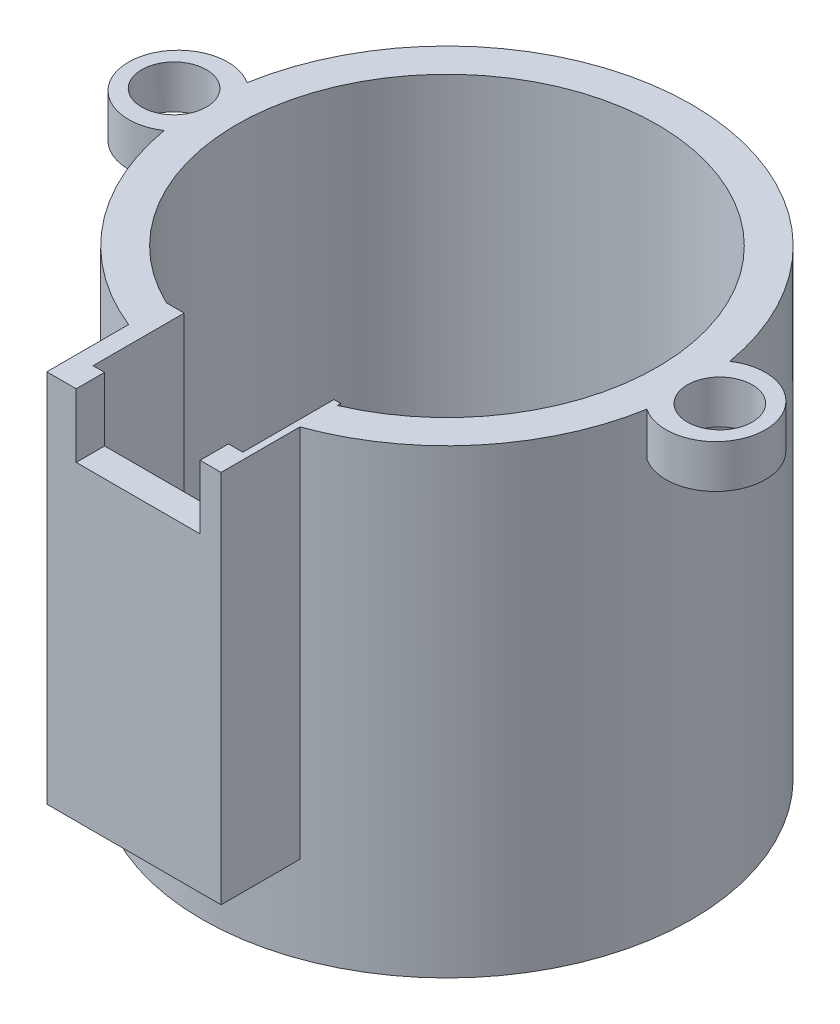
SolidWorks part; units mm, degrees
ref_plane "Front Plane" through (0, 0, 0) normal (0, 0, 1) x (1, 0, 0)
ref_plane "Top Plane" through (0, 0, 0) normal (0, 1, 0) x (1, 0, 0)
ref_plane "Right Plane" through (0, 0, 0) normal (1, 0, 0) x (0, 0, -1)
sketch "Sketch1" plane through (0, 0, 0) normal (0, 1, 0) x (1, 0, 0)
  circle A0 centre (0, 0) radius 17
  dimension "D1" = 34
extrude "Boss-Extrude1" add sketch "Sketch1" along normal blind 32
shell "Shell1" thickness 2.4
sketch "Sketch2" plane through (0, 32, 0) normal (0, 1, 0) x (1, 0, 0)
  line L0 (-14.6, 0) -> (37.717, 0) construction
  line L1 (0, 0) -> (0, -36.0151) construction
  circle A0 centre (0, 0) radius 14.6 construction
  circle A3 centre (18.6594, 0) radius 3.45
  circle A4 centre (-18.6594, 0) radius 3.45
  point P6 (18.6594, 0)
extrude "Boss-Extrude3" add sketch "Sketch2" against normal blind 3
sketch "Sketch4" plane through (0, 32, 0) normal (0, 1, 0) x (1, 0, 0)
  line L0 (0, 0) -> (0, -29.7272) construction
  circle A0 centre (18.9465, 0) radius 2.25
  circle A1 centre (-18.9465, 0) radius 2.25
  dimension "D1" = 4.5
extrude "Cut-Extrude1" cut sketch "Sketch4" against normal blind 3
sketch "Sketch5" plane through (0, 32, 0) normal (0, 1, 0) x (1, 0, 0)
  line L1 (-6.3219, -13.1603) -> (5.7781, -13.1603)
  line L2 (-6.3219, -13.1603) -> (-6.3219, -21.4603)
  line L3 (-6.3219, -21.4603) -> (5.7781, -21.4603)
  line L4 (5.7781, -13.1603) -> (5.7781, -21.4603)
  circle A0 centre (0, 0) radius 14.6 construction
  dimension "D1" = 12.1
  dimension "D2" = 8.3
extrude "Boss-Extrude4" add sketch "Sketch5" against normal blind 26
sketch "Sketch6" plane through (0, 32, 0) normal (0, 1, 0) x (1, 0, 0)
  line L1 (-5.0834, -19.4896) -> (5.3166, -19.4896)
  line L2 (-5.0834, -19.4896) -> (-5.0834, -10.8896)
  line L3 (-5.0834, -10.8896) -> (5.3166, -10.8896)
  line L4 (5.3166, -19.4896) -> (5.3166, -10.8896)
  point P4 (-5.0026, -19.4358)
  point P5 (5.3166, -19.4896)
  dimension "D1" = 10.4
  dimension "D2" = 8.6
extrude "Cut-Extrude2" cut sketch "Sketch6" against normal blind 25
sketch "Sketch7" plane through (0, 0, 21.4603) normal (0, 0, 1) x (1, 0, 0)
  line L1 (-4.2805, 27.5726) -> (4.3195, 27.5726)
  line L2 (-4.2805, 27.5726) -> (-4.2805, 33.3726)
  line L3 (-4.2805, 33.3726) -> (4.3195, 33.3726)
  line L4 (4.3195, 27.5726) -> (4.3195, 33.3726)
  dimension "D1" = 8.6
  dimension "D2" = 5.8
extrude "Cut-Extrude3" cut sketch "Sketch7" against normal blind 5
